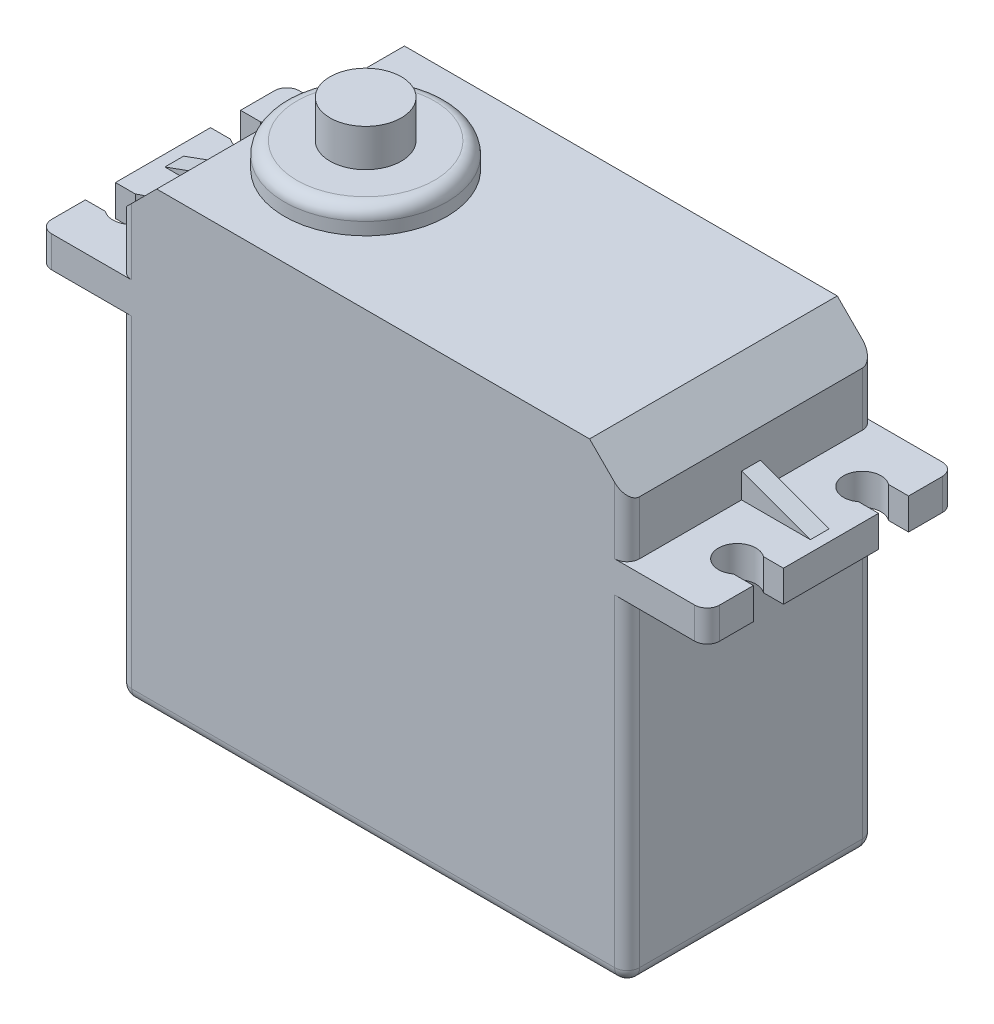
SolidWorks part; units mm, degrees
ref_plane "Front Plane" through (0, 0, 0) normal (0, 0, 1) x (1, 0, 0)
ref_plane "Top Plane" through (0, 0, 0) normal (0, 1, 0) x (1, 0, 0)
ref_plane "Right Plane" through (0, 0, 0) normal (1, 0, 0) x (0, 0, -1)
sketch "Sketch1" plane through (0, 0, 0) normal (0, 0, 1) x (1, 0, 0)
  line L0 (0, 0) -> (40.6, 0)
  line L1 (0, 0) -> (0, 26.8)
  line L2 (0, 26.8) -> (-6.4, 26.8)
  line L3 (-6.4, 26.8) -> (-6.4, 29.3)
  line L4 (-6.4, 29.3) -> (0, 29.3)
  line L5 (0, 29.3) -> (0, 33.6)
  line L6 (3, 36.6) -> (37.6, 36.6)
  line L7 (40.6, 33.6) -> (40.6, 29.3)
  line L8 (40.6, 29.3) -> (47, 29.3)
  line L9 (47, 29.3) -> (47, 26.8)
  line L10 (47, 26.8) -> (40.6, 26.8)
  line L11 (40.6, 26.8) -> (40.6, 0)
  line L12 (0, 33.6) -> (3, 36.6)
  line L13 (37.6, 36.6) -> (40.6, 33.6)
  point P7 (0, 36.6)
  point P8 (40.6, 36.6)
  dimension "D1" = 40.6
  dimension "D2" = 26.8
  dimension "D3" = 2.5
  dimension "D4" = 36.6
  dimension "D5" = 53.4
extrude "Main Servo Body" add sketch "Sketch1" along normal blind 19.8
sketch "Sketch2" plane through (0, 29.3, 0) normal (0, 1, 0) x (1, 0, 0)
  line L0 (-6.4, -19.8) -> (-6.4, 0) construction
  line L1 (47, -19.8) -> (47, 0) construction
  line L2 (-6.4, -3.7) -> (-4.8, -3.7)
  line L3 (-6.4, -6.1) -> (-4.8, -6.1)
  line L4 (-6.4, -3.7) -> (-6.4, -6.1)
  line L5 (45.4, -3.7) -> (47, -3.7)
  line L6 (47, -3.7) -> (47, -6.1)
  line L7 (45.4, -13.7) -> (47, -13.7)
  line L8 (45.4, -6.1) -> (47, -6.1)
  line L9 (47, -16.1) -> (47, -13.7)
  line L10 (45.4, -16.1) -> (47, -16.1)
  line L11 (-6.4, -16.1) -> (-6.4, -13.7)
  line L12 (-6.4, -13.7) -> (-4.8, -13.7)
  line L13 (-6.4, -16.1) -> (-4.8, -16.1)
  line L14 (-6.4, -9.9) -> (47, -9.9) construction
  line L15 (0, -19.8) -> (0, 0) construction
  arc A0 (45.4, -3.7) -> (45.4, -6.1) centre (44.5, -4.9) ccw
  arc A1 (-4.8, -6.1) -> (-4.8, -3.7) centre (-3.9, -4.9) ccw
  arc A2 (-4.8, -13.7) -> (-4.8, -16.1) centre (-3.9, -14.9) cw
  arc A3 (45.4, -16.1) -> (45.4, -13.7) centre (44.5, -14.9) cw
  dimension "D1" = 3
  dimension "D2" = 5
  dimension "D3" = 2.5
  dimension "D4" = 2.5
  dimension "D5" = 2.4
  dimension "D6" = 2.4
extrude "Servo Bracket" cut sketch "Sketch2" against normal through all
sketch "Sketch3" plane through (0, 36.6, 0) normal (0, 1, 0) x (1, 0, 0)
  circle A0 centre (10, -10.1) radius 6.5
  dimension "D1" = 13
  dimension "D2" = 10
  dimension "D3" = 10.1
extrude "Servo Axis 1" add sketch "Sketch3" along normal blind 2
ref_plane "Plane for Servo Brackets Support" through (0, 0, 9.9) normal (0, 0, 1) x (1, 0, 0)
sketch "Sketch4" plane through (0, 0, 9.9) normal (0, 0, 1) x (1, 0, 0)
  line L0 (-5.5, 29.3) -> (0, 31.3)
  line L1 (0, 29.3) -> (-6.4, 29.3) construction
  line L2 (0, 33.6) -> (0, 29.3) construction
  line L3 (0, 31.3) -> (0, 29.3)
  line L4 (0, 29.3) -> (-5.5, 29.3)
  line L5 (40.6, 29.3) -> (46.1, 29.3)
  line L7 (46.1, 29.3) -> (40.6, 31.3)
  line L9 (40.6, 31.3) -> (40.6, 29.3)
  line L10 (47, 29.3) -> (40.6, 29.3) construction
  dimension "D1" = 5.5
  dimension "D2" = 2
extrude "Servo Bracket Support" add sketch "Sketch4" along normal mid plane 1.5
sketch "Sketch5" plane through (0, 38.6, 0) normal (0, 1, 0) x (1, 0, 0)
  circle A0 centre (10, -10.1) radius 2.85
  circle A1 centre (10, -10.1) radius 6.5 construction
  dimension "D1" = 5.7
extrude "Servo Axis 2" add sketch "Sketch5" along normal blind 3
sketch "Sketch6" plane through (0, 0, 0) normal (-1, 0, 0) x (0, 0, 1)
  circle A0 centre (10.1, 6) radius 2.5
  dimension "D1" = 5
  dimension "D2" = 10.1
  dimension "D3" = 6
extrude "Servo Wires" add sketch "Sketch6" along normal blind 2
fillet "Servo Contouring" radius 1 17 edges at (-6.4, 28.05, 19.8) (10, 38.6, 16.6) (-6.4, 28.05, 0) (0, 13.4, 0) (47, 28.05, 0) (47, 28.05, 19.8) (40.6, 13.4, 0) (40.6, 13.4, 19.8) (40.6, 0, 9.9) (20.3, 0, 0) (0, 0, 9.9) (20.3, 0, 19.8) (0, 13.4, 19.8) (40.6, 31.45, 0) (40.6, 31.45, 19.8) (0, 31.45, 0) (0, 31.45, 19.8)
